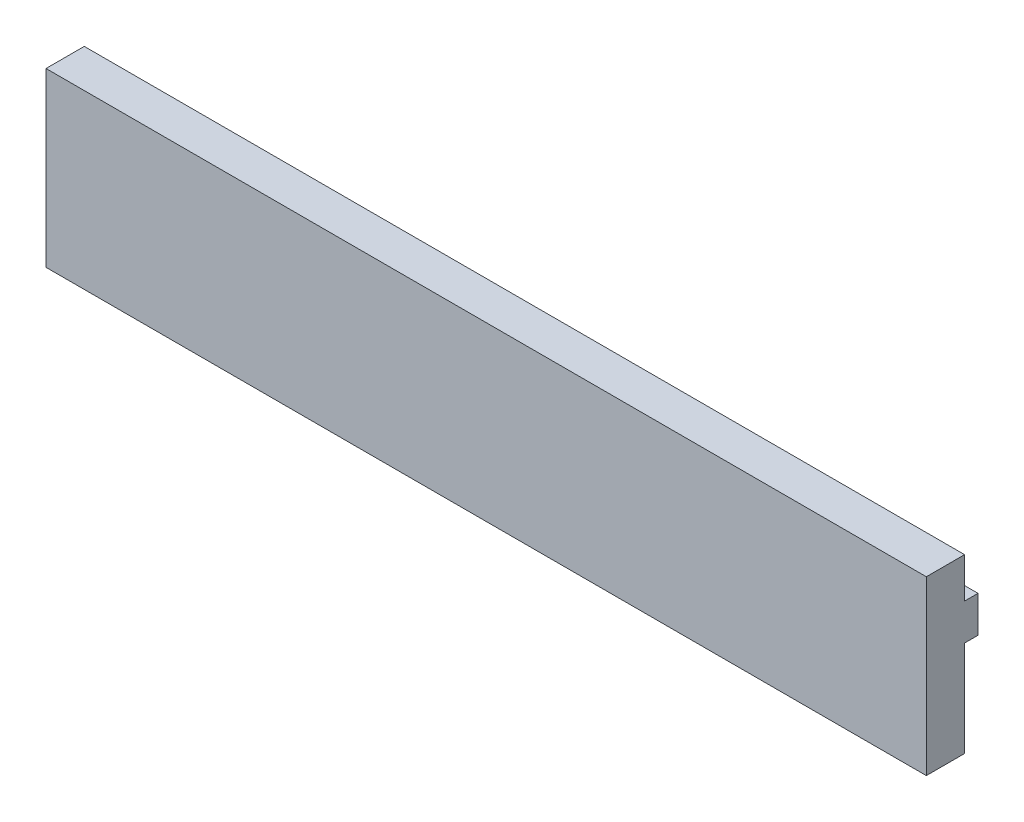
SolidWorks part; units mm, degrees
ref_plane "Alzado" through (0, 0, 0) normal (0, 0, 1) x (1, 0, 0)
ref_plane "Planta" through (0, 0, 0) normal (0, 1, 0) x (1, 0, 0)
ref_plane "Vista lateral" through (0, 0, 0) normal (1, 0, 0) x (0, 0, -1)
sketch "Croquis1" plane through (0, 0, 0) normal (0, 0, 1) x (1, 0, 0)
  line L1 (230, -45) -> (-230, -45)
  line L2 (230, -45) -> (230, 45)
  line L3 (230, 45) -> (-230, 45)
  line L4 (-230, -45) -> (-230, 45)
  line L5 (230, -45) -> (-230, 45) construction
  line L6 (230, 45) -> (-230, -45) construction
  point P0 (0, 0)
  dimension "D1" = 460
  dimension "D2" = 90
extrude "Saliente-Extruir1" add sketch "Croquis1" along normal blind 20
sketch "Croquis3" plane through (0, 0, 0) normal (0, 0, -1) x (-1, 0, 0)
  line L0 (230, 45) -> (230, -45) construction
  line L1 (-230, 24) -> (230, 24)
  line L2 (-230, 24) -> (-230, 5)
  line L3 (-230, 5) -> (230, 5)
  line L4 (230, 24) -> (230, 5)
  line L5 (-230, 24) -> (230, 5) construction
  line L6 (-230, 5) -> (230, 24) construction
  line L7 (-230, 45) -> (230, 45) construction
  point P0 (0, 14.5)
  dimension "D1" = 21
  dimension "D2" = 19
  dimension "D3" = 460
extrude "Saliente-Extruir3" add sketch "Croquis3" along normal blind 7
